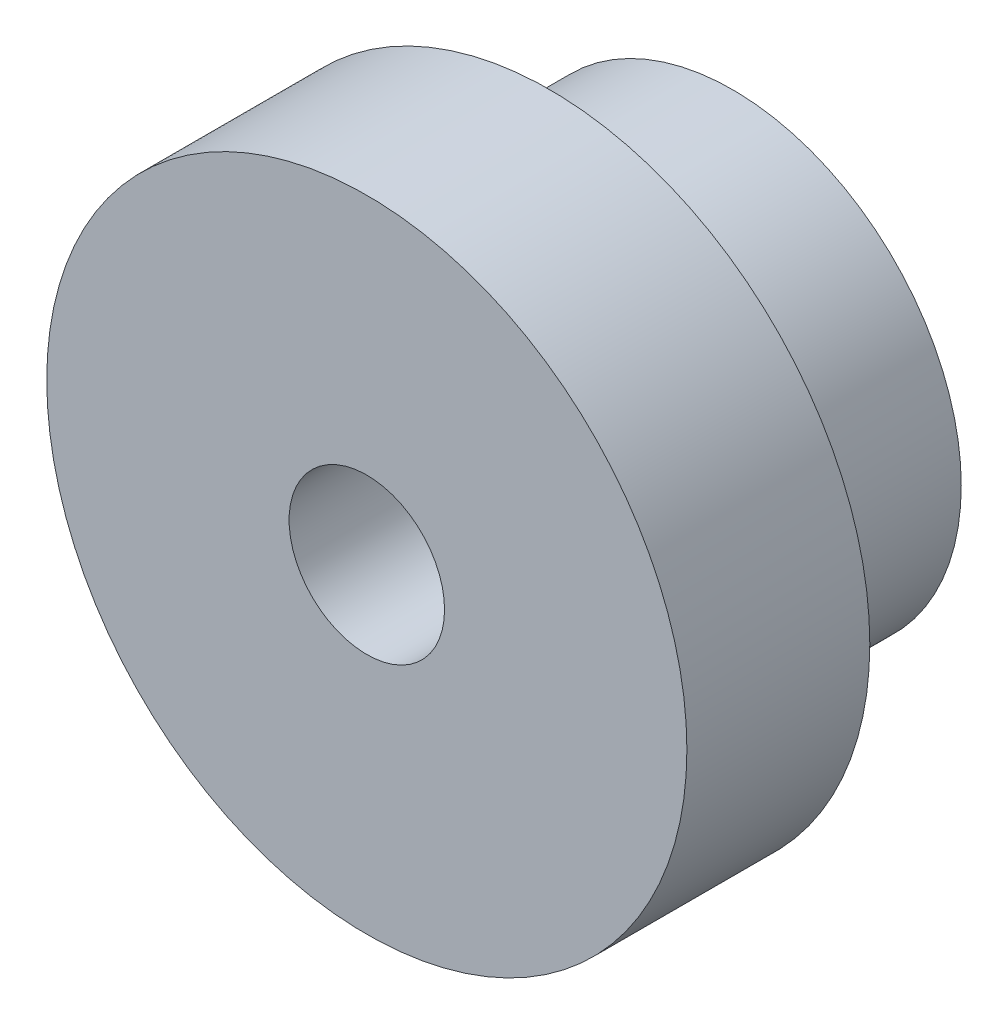
SolidWorks part; units mm, degrees
material "7075-O (SS)"
ref_plane "Front" through (0, 0, 0) normal (0, 0, 1) x (1, 0, 0)
ref_plane "Top" through (0, 0, 0) normal (0, 1, 0) x (1, 0, 0)
ref_plane "Right" through (0, 0, 0) normal (1, 0, 0) x (0, 0, -1)
sketch "Croquis1" plane through (0, 0, 0) normal (0, 0, 1) x (1, 0, 0)
  circle A0 centre (0, 0) radius 5
  dimension "D1" = 10
extrude "Saliente-Extruir1" add sketch "Croquis1" along normal blind 4
sketch "Croquis2" plane through (0, 0, 4) normal (0, 0, 1) x (1, 0, 0)
  circle A0 centre (0, 0) radius 7
  dimension "D1" = 14
extrude "Saliente-Extruir2" add sketch "Croquis2" along normal blind 4
hole_wizard "Taladro de margen para M31" positions "Croquis3" profile "Croquis5" hole size "M3" standard "Ansi Metric" end condition up to next
sketch "Croquis3" plane through (0, 0, 8) normal (0, 0, 1) x (1, 0, 0)
  point P0 (0, 0)
sketch "Croquis5" plane through (0, 0, 8) normal (1, 0, 0) x (0, -1, 0)
  line L0 (0, 0) -> (0, 8)
  line L1 (0, 8) -> (1.7, 8)
  line L2 (1.7, 8) -> (1.7, 0)
  line L5 (1.7, 0) -> (0, 0)
  line L11 (0, -6.35) -> (0, 107.95) construction
  dimension "Diámetro de taladro hasta el siguiente" = 3.4
  dimension "Profundidad de taladro hasta el siguiente" = 8
